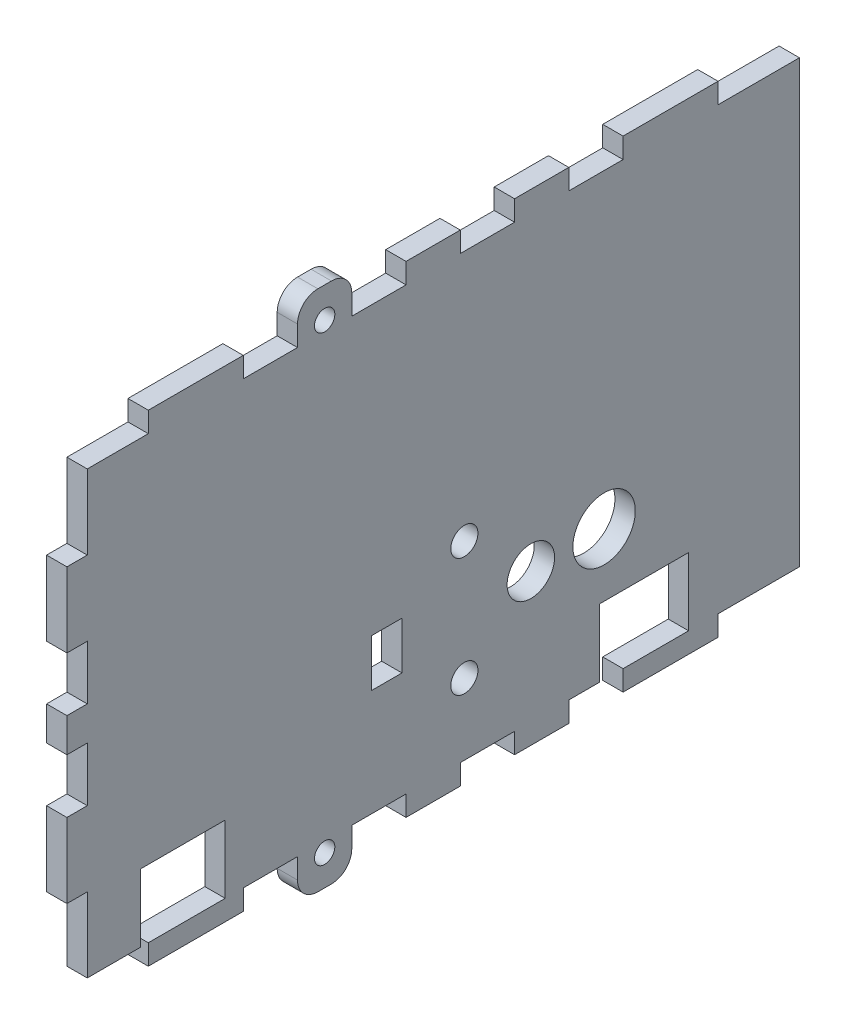
SolidWorks part; units mm, degrees
material "Balsa"
ref_plane "Alzado" through (0, 0, 0) normal (0, 0, 1) x (1, 0, 0)
ref_plane "Planta" through (0, 0, 0) normal (0, 1, 0) x (1, 0, 0)
ref_plane "Vista lateral" through (0, 0, 0) normal (1, 0, 0) x (0, 0, -1)
sketch "Croquis1" plane through (0, 0, 0) normal (1, 0, 0) x (0, 0, -1)
  line L1 (-54, -35.5) -> (54, -35.5)
  line L2 (-54, -35.5) -> (-54, 35.5)
  line L3 (-54, 35.5) -> (54, 35.5)
  line L4 (54, -35.5) -> (54, 35.5)
  line L5 (-54, -35.5) -> (54, 35.5) construction
  line L6 (-54, 35.5) -> (54, -35.5) construction
  point P0 (0, 0)
  dimension "D1" = 108
  dimension "D2" = 71
extrude "Saliente-Extruir1" add sketch "Croquis1" along normal mid plane 3
sketch "Croquis2" plane through (-1.5, 0, 0) normal (-1, 0, 0) x (0, 0, 1)
  line L0 (54, -35.5) -> (-54, -35.5) construction
  line L1 (-42, -32.5) -> (-54, -32.5)
  line L2 (-42, -32.5) -> (-42, -35.5)
  line L3 (-42, -35.5) -> (-54, -35.5)
  line L4 (-54, -32.5) -> (-54, -35.5)
  line L5 (-28, -32.5) -> (-20, -32.5)
  line L6 (-28, -32.5) -> (-28, -35.5)
  line L7 (-28, -35.5) -> (-20, -35.5)
  line L8 (-20, -32.5) -> (-20, -35.5)
  line L9 (-20, -32.5) -> (-20, -35.5) construction
  line L10 (-4, -32.5) -> (-4, -35.5) construction
  line L11 (-12, -32.5) -> (-4, -32.5)
  line L12 (-12, -32.5) -> (-12, -35.5)
  line L13 (-12, -35.5) -> (-4, -35.5)
  line L14 (-4, -32.5) -> (-4, -35.5)
  line L15 (12, -32.5) -> (12, -35.5) construction
  line L16 (4, -32.5) -> (12, -32.5)
  line L17 (4, -32.5) -> (4, -35.5)
  line L18 (4, -35.5) -> (12, -35.5)
  line L19 (12, -32.5) -> (12, -35.5)
  line L20 (28, -32.5) -> (28, -35.5) construction
  line L21 (20, -32.5) -> (28, -32.5)
  line L22 (20, -32.5) -> (20, -35.5)
  line L23 (20, -35.5) -> (28, -35.5)
  line L24 (28, -32.5) -> (28, -35.5)
  line L25 (-54, 0) -> (54, 0) construction
  line L26 (42, -32.5) -> (54, -32.5)
  line L27 (42, -32.5) -> (42, -35.5)
  line L28 (42, -35.5) -> (54, -35.5)
  line L29 (54, -32.5) -> (54, -35.5)
  line L30 (-54, -35.5) -> (-54, 35.5) construction
  line L31 (54, 35.5) -> (54, -35.5) construction
  line L32 (54, 32.5) -> (54, 35.5)
  line L33 (42, 35.5) -> (54, 35.5)
  line L34 (42, 32.5) -> (42, 35.5)
  line L35 (42, 32.5) -> (54, 32.5)
  line L36 (28, 32.5) -> (28, 35.5)
  line L37 (20, 35.5) -> (28, 35.5)
  line L38 (20, 32.5) -> (20, 35.5)
  line L39 (20, 32.5) -> (28, 32.5)
  line L40 (12, 32.5) -> (12, 35.5)
  line L41 (4, 35.5) -> (12, 35.5)
  line L42 (4, 32.5) -> (4, 35.5)
  line L43 (4, 32.5) -> (12, 32.5)
  line L44 (-4, 32.5) -> (-4, 35.5)
  line L45 (-12, 35.5) -> (-4, 35.5)
  line L46 (-12, 32.5) -> (-12, 35.5)
  line L47 (-12, 32.5) -> (-4, 32.5)
  line L48 (-20, 32.5) -> (-20, 35.5)
  line L49 (-28, 35.5) -> (-20, 35.5)
  line L50 (-28, 32.5) -> (-28, 35.5)
  line L51 (-28, 32.5) -> (-20, 32.5)
  line L52 (-54, 32.5) -> (-54, 35.5)
  line L53 (-42, 35.5) -> (-54, 35.5)
  line L54 (-42, 32.5) -> (-42, 35.5)
  line L55 (-42, 32.5) -> (-54, 32.5)
extrude "Cortar-Extruir1" cut sketch "Croquis2" against normal blind 3
sketch "Croquis6" plane through (-1.5, 0, 0) normal (-1, 0, 0) x (0, 0, 1)
  line L0 (54, 32.5) -> (54, -32.5) construction
  line L1 (51, -21.5) -> (54, -21.5)
  line L2 (51, -21.5) -> (51, -35.5)
  line L3 (51, -35.5) -> (54, -35.5)
  line L4 (54, -21.5) -> (54, -35.5)
  line L5 (51, -2.5) -> (54, -2.5)
  line L6 (51, -2.5) -> (51, -10.5)
  line L7 (51, -10.5) -> (54, -10.5)
  line L8 (54, -2.5) -> (54, -10.5)
  line L9 (51, -10.5) -> (54, -10.5) construction
  line L10 (51, 10.5) -> (54, 10.5) construction
  line L11 (51, 2.5) -> (54, 2.5)
  line L12 (51, 2.5) -> (51, 10.5)
  line L13 (51, 10.5) -> (54, 10.5)
  line L14 (54, 2.5) -> (54, 10.5)
  line L16 (51, 21.5) -> (54, 21.5)
  line L17 (51, 21.5) -> (51, 35.5)
  line L18 (51, 35.5) -> (54, 35.5)
  line L19 (54, 21.5) -> (54, 35.5)
extrude "Cortar-Extruir3" cut sketch "Croquis6" against normal blind 3
sketch "Croquis8" plane through (-1.5, 0, 0) normal (-1, 0, 0) x (0, 0, 1)
  line L1 (12, 35.5) -> (20, 35.5)
  line L2 (12, 35.5) -> (12, 38.5)
  line L3 (12, 38.5) -> (20, 38.5)
  line L4 (20, 35.5) -> (20, 38.5)
  dimension "D1" = 3
extrude "Saliente-Extruir2" add sketch "Croquis8" against normal blind 3
fillet "Redondeo2" radius 3 2 edges at (0, 38.5, 20) (0, 38.5, 12)
sketch "Croquis9" plane through (-1.5, 0, 0) normal (-1, 0, 0) x (0, 0, 1)
  line L0 (12, 34) -> (20, 34) construction
  line L1 (12, 32.5) -> (12, 35.5) construction
  line L2 (20, 35.5) -> (20, 32.5) construction
  circle A0 centre (16, 34) radius 1.5
  dimension "D1" = 3
extrude "Cortar-Extruir5" cut sketch "Croquis9" against normal blind 3
mirror "Simetría1" about plane through (0, 0, 0) normal (0, 1, 0) of "Redondeo2", "Cortar-Extruir5", "Saliente-Extruir2"
sketch "Croquis10" plane through (-1.5, 0, 0) normal (-1, 0, 0) x (0, 0, 1)
  line L1 (4.6, -16.75) -> (9.1, -16.75)
  line L2 (4.6, -16.75) -> (4.6, -9.75)
  line L3 (4.6, -9.75) -> (9.1, -9.75)
  line L4 (9.1, -16.75) -> (9.1, -9.75)
  circle A0 centre (-25.2, -13.25) radius 4.6
  circle A1 centre (-14.4, -13.25) radius 3.5
  circle A2 centre (-4.6, -22) radius 2
  circle A3 centre (-4.6, -4.5) radius 2
extrude "Cortar-Extruir6" cut sketch "Croquis10" against normal blind 10
sketch "Croquis12" plane through (-1.5, 0, 0) normal (-1, 0, 0) x (0, 0, 1)
  line L1 (-37.6615, -32.5) -> (-24.5385, -32.5)
  line L2 (-37.6615, -32.5) -> (-37.6615, -22.5)
  line L3 (-37.6615, -22.5) -> (-24.5385, -22.5)
  line L4 (-24.5385, -32.5) -> (-24.5385, -22.5)
  line L5 (43.1407, -22.5) -> (30.6593, -22.5)
  line L6 (43.1407, -22.5) -> (43.1407, -32.5)
  line L7 (43.1407, -32.5) -> (30.6593, -32.5)
  line L8 (30.6593, -22.5) -> (30.6593, -32.5)
extrude "Cortar-Extruir7" cut sketch "Croquis12" against normal blind 10
